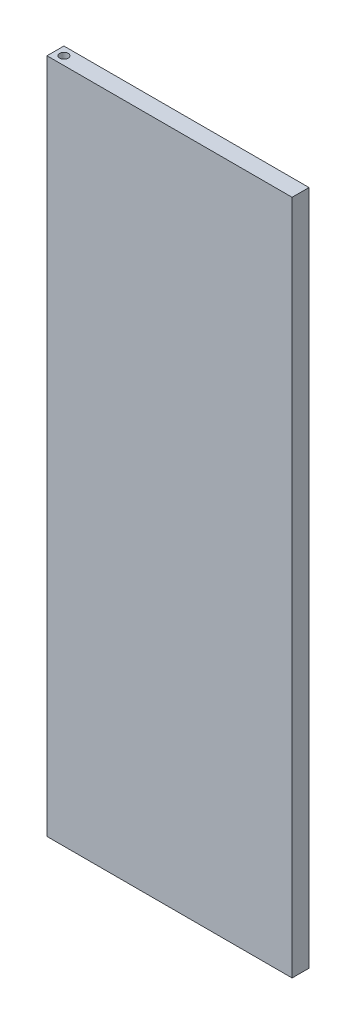
SolidWorks part; units mm, degrees
ref_plane "Front Plane" through (0, 0, 0) normal (0, 0, 1) x (1, 0, 0)
ref_plane "Top Plane" through (0, 0, 0) normal (0, 1, 0) x (1, 0, 0)
ref_plane "Right Plane" through (0, 0, 0) normal (1, 0, 0) x (0, 0, -1)
sketch "Sketch1" plane through (0, 0, 0) normal (0, 1, 0) x (1, 0, 0)
  line L1 (0, 0) -> (-725, 0)
  line L2 (0, 0) -> (0, 50)
  line L3 (0, 50) -> (-725, 50)
  line L4 (-725, 0) -> (-725, 50)
  dimension "D1" = 725
  dimension "D2" = 50
extrude "Boss-Extrude1" add sketch "Sketch1" against normal blind 2000
sketch "Sketch2" plane through (0, 0, 0) normal (0, 1, 0) x (1, 0, 0)
  line L0 (-725, 50) -> (-725, 0) construction
  line L1 (0, 50) -> (-725, 50) construction
  circle A0 centre (-700, 25) radius 12.5
  point P2 (-725, 25)
  dimension "D3" = 25
  dimension "D1" = 25
  dimension "D2" = 25
extrude "Cut-Extrude1" cut sketch "Sketch2" against normal blind 100 contours A0
